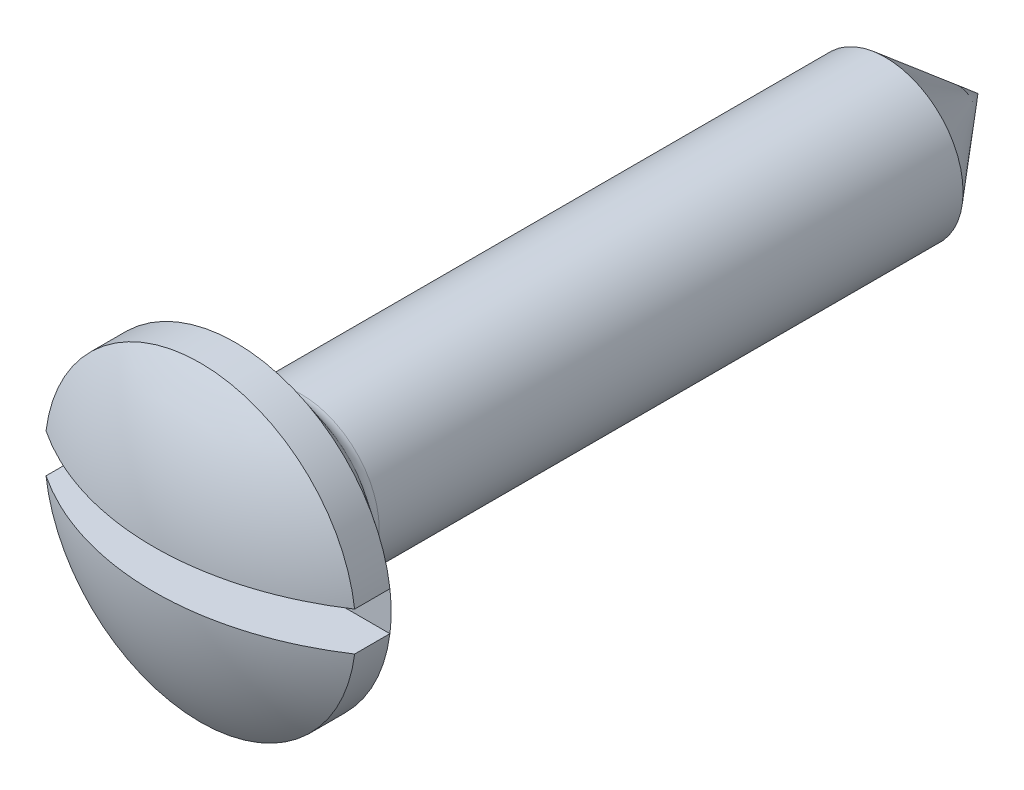
SolidWorks part; units mm, degrees
material "镍"
ref_plane "前视基准面" through (0, 0, 0) normal (0, 0, 1) x (1, 0, 0)
ref_plane "上视基准面" through (0, 0, 0) normal (0, 1, 0) x (1, 0, 0)
ref_plane "右视基准面" through (0, 0, 0) normal (1, 0, 0) x (0, 0, -1)
sketch "草图1" plane through (0, 0, 0) normal (1, 0, 0) x (0, 0, -1)
  line L0 (0, 0) -> (10.6067, 0)
  line L1 (10.6067, 0) -> (9.4149, 1)
  line L2 (9.4149, 1) -> (1.9069, 1)
  line L3 (1.7467, 1.0803) -> (1.06, 2)
  line L4 (1.06, 2) -> (0.6067, 2)
  line L5 (0, 0) -> (4.6067, 0) construction
  line L6 (0, 0) -> (0, -0.25) construction
  line L7 (4.6067, 1) -> (4.6067, 0) construction
  line L8 (0, -0.25) -> (0.6, -0.25) construction
  arc A0 (0, 0) -> (0.6067, 2) centre (3.6, 0) cw
  arc A1 (1.9069, 1) -> (1.7467, 1.0803) centre (1.9069, 1.2) cw
  point P11 (1.8067, 1)
  dimension "rf" = 3.6
  dimension "r" = 0.2
  dimension "d" = 2
  dimension "dk" = 4
  dimension "l0" = 6
  dimension "k" = 1.2
  dimension "t" = 1.06
  dimension "D9" = 40
  dimension "l" = 10
  dimension "n" = 0.5
  dimension "f" = 0.6
revolve "旋转1" add sketch "草图1" angle 360 about L5
cosmetic thread "装饰螺纹线1" parameters "D1"=6, "D2"=1.732
sketch "草图2" plane through (0, 0, 0) normal (0, 0, 1) x (1, 0, 0)
  line L0 (5, 0.25) -> (-5, 0.25)
  line L1 (-5, 0.25) -> (-5, -0.25)
  line L2 (-5, -0.25) -> (5, -0.25)
  line L3 (5, -0.25) -> (5, 0.25)
  line L4 (0, 0.25) -> (0, -0.25) construction
  dimension "D1" = 10
  dimension "D2" = 0.5
extrude "切除-拉伸1" cut sketch "草图2" against normal up to vertex (1.06 mm away) up to point (0, 2, -1.06)
sketch "草图4" plane through (0, 0, 0) normal (1, 0, 0) x (0, 0, -1)
  line L0 (4.6067, 1) -> (4.8567, 1)
  line L1 (9.4149, 1) -> (1.9069, 1) construction
  line L2 (4.8567, 1) -> (4.7793, 0.866)
  line L3 (4.7793, 0.866) -> (4.684, 0.866)
  line L4 (4.684, 0.866) -> (4.6067, 1)
  line L5 (4.7317, 1) -> (4.7317, 0.866) construction
  line L6 (1.9069, 0) -> (10.6067, 0) construction
  line L7 (1.9069, 1) -> (1.9069, -1) construction
  dimension "D1" = 1.732
  dimension "D2" = 60
  dimension "D3" = 0.25
revolve "切除-旋转1" [suppressed] cut sketch "草图4" angle 360 about L6
pattern_linear "阵列(线性)2" [suppressed] count 22 spacing 0.275 along (0, 0, -1)
